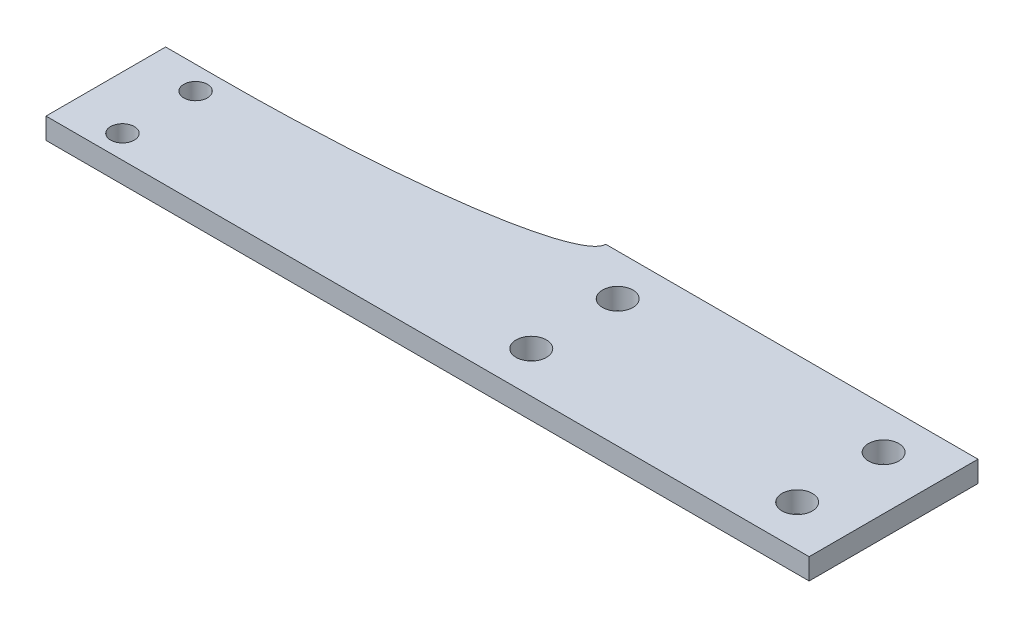
SolidWorks part; units mm, degrees
ref_plane "Front Plane" through (0, 0, 0) normal (0, 0, 1) x (1, 0, 0)
ref_plane "Top Plane" through (0, 0, 0) normal (0, 1, 0) x (1, 0, 0)
ref_plane "Right Plane" through (0, 0, 0) normal (1, 0, 0) x (0, 0, -1)
sketch "Sketch1" plane through (0, 0, 0) normal (0, 1, 0) x (1, 0, 0)
  line L0 (-26.7, -6.35) -> (-26.7, 2.65) construction
  line L1 (-26.7, -6.35) -> (26.7, -6.35)
  line L2 (-26.7, -6.35) -> (-26.7, 6.35) construction
  line L3 (-26.7, 6.35) -> (26.7, 6.35) construction
  line L4 (26.7, -6.35) -> (26.7, 6.35)
  line L5 (-26.7, -6.35) -> (26.7, 6.35) construction
  line L6 (-26.7, 6.35) -> (26.7, -6.35) construction
  line L7 (26.7, 6.35) -> (-1.3, 6.35)
  line L8 (-26.7, -6.35) -> (-30.7, -6.35)
  line L9 (-30.7, -6.35) -> (-30.7, 2.65)
  line L10 (-30.7, 2.65) -> (-26.7, 2.65)
  line L11 (-26.7, 0.9) -> (-26.7, 2.65) construction
  line L12 (-26.7, -4.6) -> (-26.7, -6.35) construction
  line L13 (2.7, 6.35) -> (2.7, -6.35) construction
  line L14 (22.7, 6.35) -> (22.7, -6.35) construction
  line L15 (2.7, -3.25) -> (2.7, -6.35) construction
  line L16 (2.7, 3.25) -> (2.7, 6.35) construction
  line L17 (2.7, 3.25) -> (22.7, 3.25) construction
  line L18 (2.7, -3.25) -> (22.7, -3.25) construction
  circle A0 centre (-26.7, 0.9) radius 0.89
  circle A1 centre (-26.7, -4.6) radius 0.89
  circle A2 centre (2.7, 3.25) radius 1.143
  circle A3 centre (2.7, -3.25) radius 1.143
  circle A4 centre (22.7, 3.25) radius 1.143
  circle A5 centre (22.7, -3.25) radius 1.143
  ellipse E0 centre (-26.7, 6.35) end of major axis (-1.3, 6.35) minor radius 3.7 (-26.7, 2.65) -> (-1.3, 6.35) ccw
  point P0 (0, 0)
  dimension "D6" = 1.78
  dimension "D10" = 2.286
  dimension "D1" = 12.7
  dimension "D2" = 53.4
  dimension "D3" = 9
  dimension "D4" = 25.4
  dimension "D5" = 4
  dimension "D7" = 5.5
  dimension "D8" = 4
  dimension "D9" = 20
  dimension "D11" = 6.5
extrude "Boss-Extrude1" add sketch "Sketch1" along normal blind 1.5875
